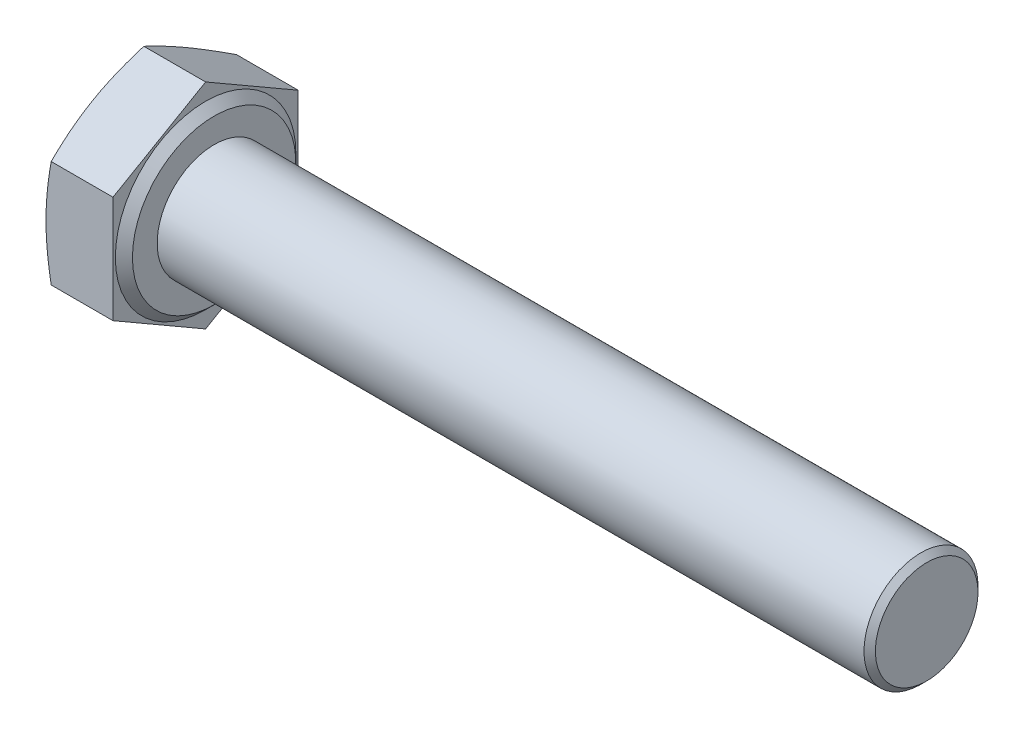
SolidWorks part; units mm, degrees
material "304 Stainless Steel"
ref_plane "Front" through (0, 0, 0) normal (0, 0, 1) x (1, 0, 0)
ref_plane "Top" through (0, 0, 0) normal (0, 1, 0) x (1, 0, 0)
ref_plane "Right" through (0, 0, 0) normal (1, 0, 0) x (0, 0, -1)
sketch "Sketch2" plane through (0, 0, 0) normal (1, 0, 0) x (0, 0, -1)
  line L1 (0, -7.5056) -> (6.5, -3.7528)
  line L2 (6.5, -3.7528) -> (6.5, 3.7528)
  line L3 (6.5, 3.7528) -> (0, 7.5056)
  line L4 (0, 7.5056) -> (-6.5, 3.7528)
  line L5 (-6.5, 3.7528) -> (-6.5, -3.7528)
  line L6 (-6.5, -3.7528) -> (0, -7.5056)
  circle A0 centre (0, 0) radius 6.5 construction
  dimension "s" = 13
extrude "BaseHead" add sketch "Sketch2" along normal blind 5.3
sketch "Sketch3" plane through (0, 0, 0) normal (0, 0, 1) x (1, 0, 0)
  line L0 (5.3, 7.5056) -> (5.3, 5.735)
  line L2 (5.3, 5.735) -> (4.7, 6.335)
  line L3 (4.7, 6.335) -> (4.7, 7.5056)
  line L5 (4.7, 7.5056) -> (5.3, 7.5056)
  line L6 (-0.9571, 0) -> (7.6478, 0) construction
  line L7 (5.3, 7.5056) -> (0, 7.5056) construction
  dimension "D1" = 45
  dimension "c" = 0.6
  dimension "dw" = 11.47
revolve "BearingFace" cut sketch "Sketch3" angle 360 about L6
sketch "Sketch4" plane through (0, 0, 0) normal (0, 0, 1) x (1, 0, 0)
  line L0 (-0.4935, 0) -> (3.5626, 0) construction
  line L2 (0, 7.5056) -> (0.366, 7.5056)
  line L4 (0.366, 7.5056) -> (0, 6.5)
  line L6 (0, 6.5) -> (0, 7.5056)
  line L7 (4.7, 7.5056) -> (0, 7.5056) construction
  dimension "D1" = 20
  dimension "D2" = 13
revolve "HeadChamfer" cut sketch "Sketch4" angle 360 about L0
sketch "Sketch5" plane through (5.3, 0, 0) normal (1, 0, 0) x (0, 0, -1)
  circle A0 centre (0, 0) radius 4
  dimension "d" = 8
extrude "BaseBody" add sketch "Sketch5" along normal blind 50
cosmetic thread "ThreadCosmetic1" [suppressed] parameters "D2"=6.647
chamfer "Chamfer1" distance 0.4 angle 45 1 edges at (55.3, 0, -4)
fillet "HeadFillet" [suppressed] radius 0.4
sketch "Sketch6" [suppressed] plane through (0, 0, 0) normal (0, 0, 1) x (1, 0, 0)
  line L0 (5.3, 4.5) -> (5.8, 4.5)
  line L1 (5.8, 4.5) -> (5.8, 4)
  line L2 (5.8, 4) -> (5.55, 3.567)
  line L3 (5.55, 3.567) -> (5.3, 4)
  line L4 (5.3, 4) -> (5.3, 4.5)
  line L5 (5.3, -5.815) -> (5.3, 5.815) construction
  line L6 (39.9, 4) -> (5.3, 4) construction
  dimension "D1" = 0.6765
revolve "Cut-Revolve10" [suppressed] cut sketch "Sketch6" angle 360
pattern_linear "LPattern10" [suppressed] count 61
equation "\"D2@Sketch4\" = \"s@Sketch2\""
equation "\"D1@Chamfer1\" = 0.05 * \"d@Sketch5\""
equation "\"D1@Sketch6\" =  ( \"d@Sketch5\" - \"D2@ThreadCosmetic1\" )  / 2"
equation "\"pitch@LPattern10\" = 1.2 * \"D1@Sketch6\""
equation "\"D1@LPattern10\" = (  \"l@BaseBody\"-\"D1@Chamfer1\" )  / \"pitch@LPattern10\""
